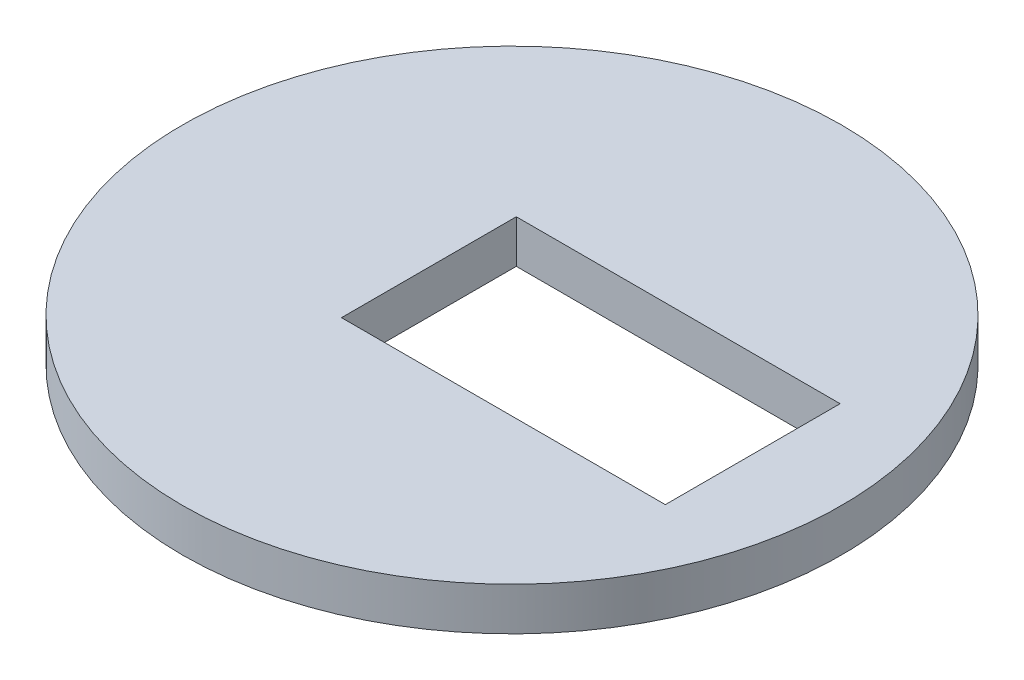
SolidWorks part; units mm, degrees
ref_plane "Front" through (0, 0, 0) normal (0, 0, 1) x (1, 0, 0)
ref_plane "Top" through (0, 0, 0) normal (0, 1, 0) x (1, 0, 0)
ref_plane "Right" through (0, 0, 0) normal (1, 0, 0) x (0, 0, -1)
sketch "Sketch1" plane through (0, 0, 0) normal (0, 1, 0) x (1, 0, 0)
  line L0 (0, 0) -> (0, -21)
  circle A2 centre (0, 0) radius 23
  dimension "D1" = 46
extrude "Boss-Extrude1" add sketch "Sketch1" along normal blind 3
sketch "Sketch2" plane through (0, 3, 0) normal (0, 1, 0) x (1, 0, 0)
  line L0 (0, 0) -> (-5.8, 0)
  line L1 (0, 0) -> (0, 6.1)
  line L2 (0, 0) -> (16.8, 0)
  line L3 (0, 0) -> (0, -6.1)
  line L5 (-5.8, 0) -> (16.8, 0)
  line L6 (-5.8, 0) -> (-5.8, -6.1)
  line L7 (-5.8, -6.1) -> (16.8, -6.1)
  line L8 (16.8, 0) -> (16.8, -6.1)
  line L9 (-5.8, 0) -> (16.8, 0)
  line L10 (-5.8, 0) -> (-5.8, 6.1)
  line L11 (-5.8, 6.1) -> (16.8, 6.1)
  line L12 (16.8, 0) -> (16.8, 6.1)
  dimension "D1" = 5.8
  dimension "D2" = 6.1
  dimension "D3" = 16.8
  dimension "D4" = 6.1
extrude "Cut-Extrude1" cut sketch "Sketch2" against normal blind 10 contours L11 L10 L0 L1 | L2 L12 L11 L1 | L8 L2 L3 L7 | L6 L7 L3 L0
